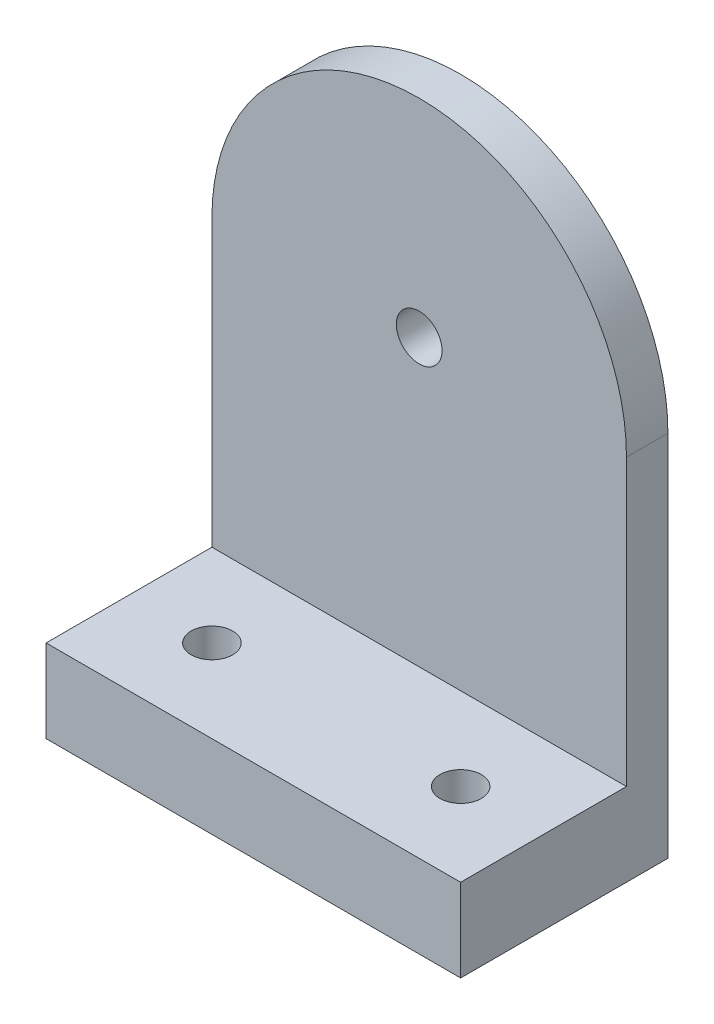
SolidWorks part; units mm, degrees
ref_plane "Front Plane" through (0, 0, 0) normal (0, 0, 1) x (1, 0, 0)
ref_plane "Top Plane" through (0, 0, 0) normal (0, 1, 0) x (1, 0, 0)
ref_plane "Right Plane" through (0, 0, 0) normal (1, 0, 0) x (0, 0, -1)
sketch "Sketch1" plane through (0, 0, 0) normal (0, 0, 1) x (1, 0, 0)
  line L1 (-15.875, 0) -> (15.875, 0)
  line L2 (-15.875, 0) -> (-15.875, -28.194)
  line L3 (-15.875, -28.194) -> (15.875, -28.194)
  line L4 (15.875, 0) -> (15.875, -28.194)
  circle A0 centre (0, 0) radius 15.875
  arc A2 (-15.875, 0) -> (15.875, 0) centre (0, 0) ccw
  dimension "D1" = 31.75
  dimension "D2" = 28.194
extrude "Boss-Extrude1" add sketch "Sketch1" along normal blind 3.175
sketch "Sketch4" plane through (0, 0, 3.175) normal (0, 0, 1) x (1, 0, 0)
  line L0 (15.875, 0) -> (15.875, -28.194) construction
  line L1 (-15.875, -28.194) -> (15.875, -28.194)
  line L2 (-15.875, -28.194) -> (-15.875, -21.844)
  line L3 (-15.875, -21.844) -> (15.875, -21.844)
  line L4 (15.875, -28.194) -> (15.875, -21.844)
  dimension "D1" = 6.35
extrude "Boss-Extrude2" add sketch "Sketch4" along normal blind 12.7
sketch "Sketch5" plane through (0, -21.844, 0) normal (0, 1, 0) x (1, 0, 0)
  line L0 (-15.875, -9.525) -> (15.875, -9.525) construction
  line L1 (-15.875, -15.875) -> (-15.875, -3.175) construction
  line L2 (15.875, -15.875) -> (15.875, -3.175) construction
  line L3 (0, -3.175) -> (0, -15.875) construction
  line L4 (15.875, -3.175) -> (-15.875, -3.175) construction
  line L5 (15.875, -15.875) -> (-15.875, -15.875) construction
  circle A0 centre (-9.525, -9.525) radius 1.5875
  circle A1 centre (9.525, -9.525) radius 1.5875
  dimension "D1" = 3.175
  dimension "D2" = 9.525
extrude "Cut-Extrude2" cut sketch "Sketch5" against normal through all
sketch "Sketch6" plane through (0, 0, 3.175) normal (0, 0, 1) x (1, 0, 0)
  circle A0 centre (0, 0) radius 1.75
  dimension "D1" = 3.5
extrude "Cut-Extrude3" cut sketch "Sketch6" against normal through all
